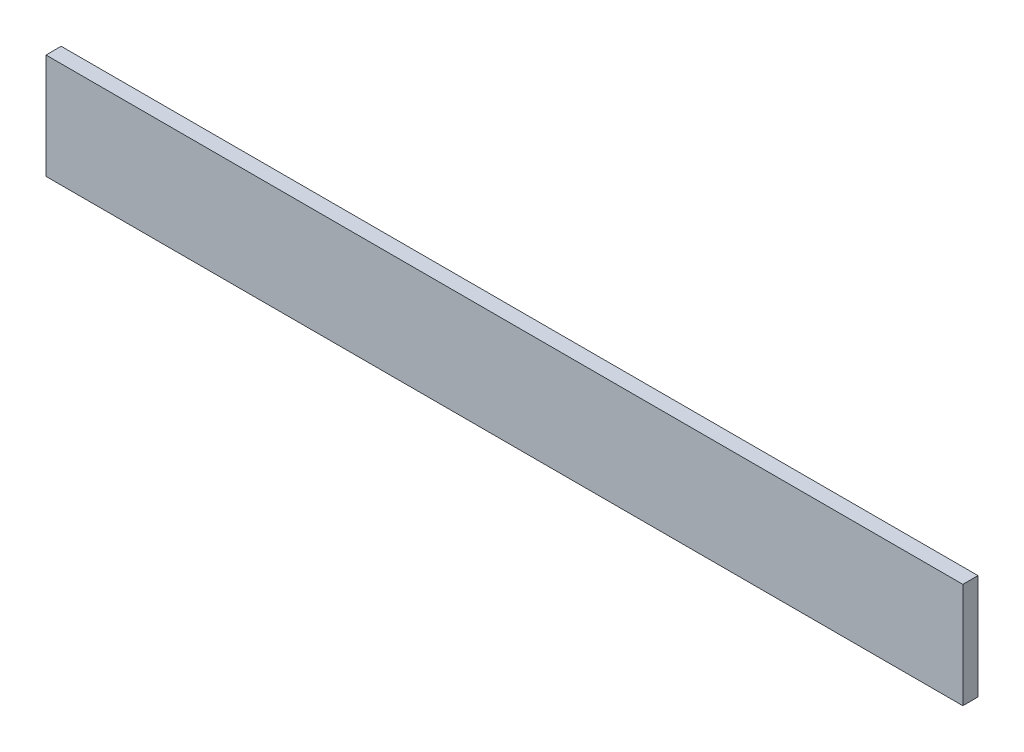
SolidWorks part; units mm, degrees
ref_plane "Спереди" through (0, 0, 0) normal (0, 0, 1) x (1, 0, 0)
ref_plane "Сверху" through (0, 0, 0) normal (0, 1, 0) x (1, 0, 0)
ref_plane "Справа" through (0, 0, 0) normal (1, 0, 0) x (0, 0, -1)
sketch "Эскиз1" plane through (0, 0, 0) normal (0, 0, 1) x (1, 0, 0)
  line L1 (-70.4678, 34.6035) -> (231.7928, 34.6035)
  line L2 (-70.4678, 34.6035) -> (-70.4678, 69.2708)
  line L3 (-70.4678, 69.2708) -> (231.7928, 69.2708)
  line L4 (231.7928, 34.6035) -> (231.7928, 69.2708)
extrude "Бобышка-Вытянуть1" add sketch "Эскиз1" along normal blind 5
